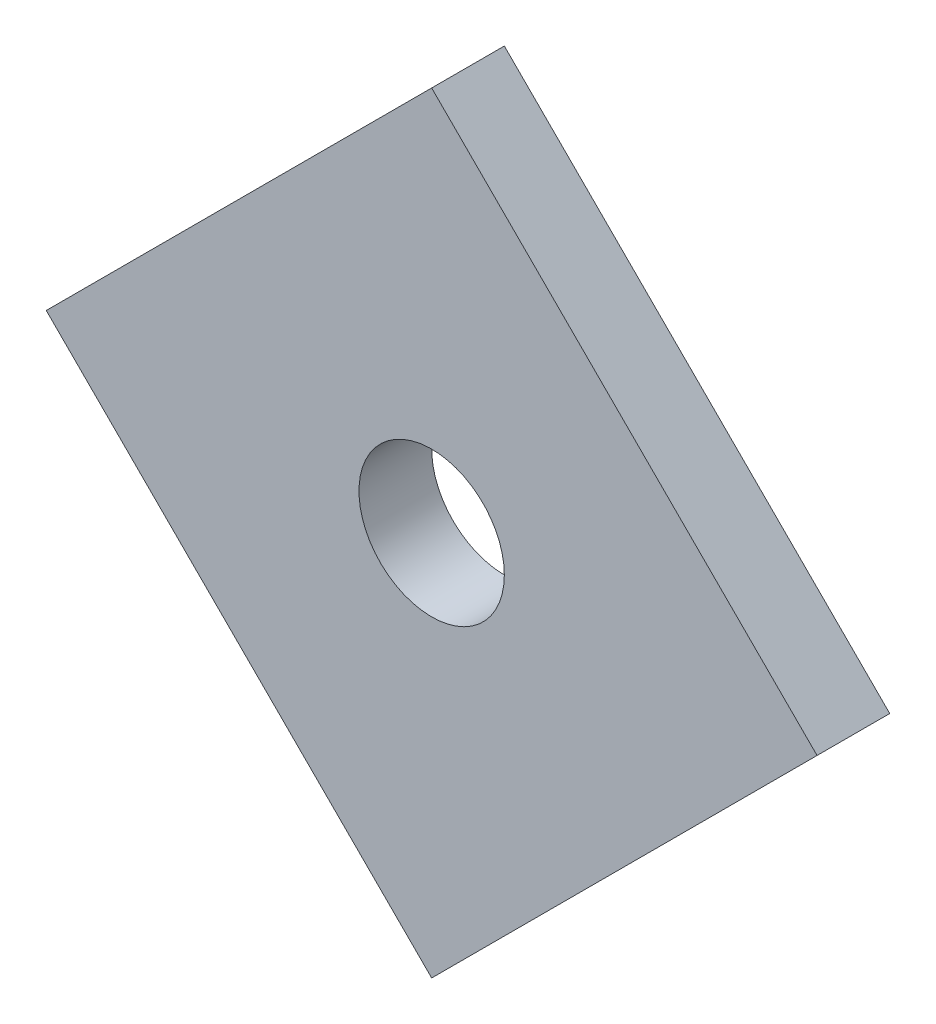
SolidWorks part; units mm, degrees
ref_plane "Alzado" through (0, 0, 0) normal (0, 0, 1) x (1, 0, 0)
ref_plane "Planta" through (0, 0, 0) normal (0, 1, 0) x (1, 0, 0)
ref_plane "Vista lateral" through (0, 0, 0) normal (1, 0, 0) x (0, 0, -1)
sketch "Croquis1" plane through (0, 0, 0) normal (0, 0, 1) x (1, 0, 0)
  line L0 (0, 0) -> (26.5165, 26.5165) construction
  line L1 (0, 0) -> (-26.5165, 26.5165) construction
  line L6 (-53.033, 0) -> (0, 53.033)
  line L7 (0, 53.033) -> (53.033, 0)
  line L8 (53.033, 0) -> (0, -53.033)
  line L9 (0, -53.033) -> (-53.033, 0)
  circle A0 centre (0, 0) radius 10
extrude "Saliente-Extruir1" add sketch "Croquis1" along normal blind 10
